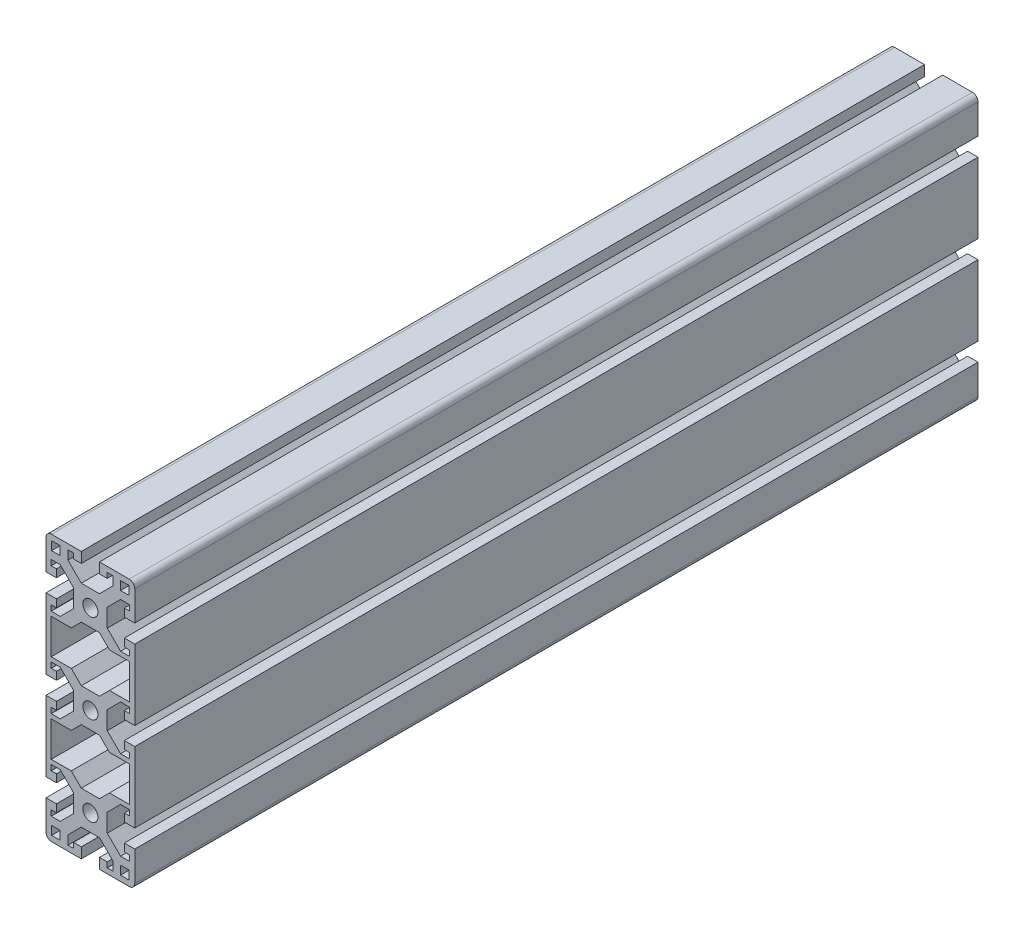
SolidWorks part; units mm, degrees
material "6063-T6"
ref_plane "Front Plane" through (0, 0, 0) normal (0, 0, 1) x (1, 0, 0)
ref_plane "Top Plane" through (0, 0, 0) normal (0, 1, 0) x (1, 0, 0)
ref_plane "Right Plane" through (0, 0, 0) normal (1, 0, 0) x (0, 0, -1)
sketch "Sketch1" plane through (0, 0, 0) normal (0, 1, 0) x (1, 0, 0)
  line L0 (0, 190) -> (0, -190)
  dimension "D1" = 380
other "40 series TS40-120LM(1)"
ref_plane "Plane1" through (0, 0, -190) normal (0, 0, 1) x (1, 0, 0)
sketch "Sketch2" plane through (0, 0, -190) normal (0, 0, 1) x (1, 0, 0)
  line L0 (15.3, -35.9) -> (20, -35.9)
  line L1 (3.35, 0) -> (7.6, 0) construction
  line L2 (7.6, 4.1) -> (7.6, -4.1)
  line L3 (7.6, -4.1) -> (13.6, -10.1)
  line L4 (13.6, -10.1) -> (17.65, -10.1)
  line L5 (17.65, -10.1) -> (17.65, -7.6)
  line L6 (17.65, -7.6) -> (15.3, -7.6)
  line L7 (15.3, -7.6) -> (15.3, -4.1)
  line L8 (15.3, -4.1) -> (20, -4.1)
  line L9 (20, -4.1) -> (20, -35.9)
  line L10 (0, -3.35) -> (0, -7.6) construction
  line L11 (-4.1, -7.6) -> (4.1, -7.6)
  line L12 (4.1, -7.6) -> (8.6, -12.1)
  line L13 (8.6, -12.1) -> (17.65, -12.1)
  line L14 (17.65, -12.1) -> (17.65, -27.9)
  line L15 (20, -20) -> (0, 0) construction
  line L16 (17.65, -20) -> (20, -20) construction
  line L17 (15.3, -32.4) -> (15.3, -35.9)
  line L18 (17.65, -32.4) -> (15.3, -32.4)
  line L19 (17.65, -29.9) -> (17.65, -32.4)
  line L20 (13.6, -29.9) -> (17.65, -29.9)
  line L21 (8.6, -27.9) -> (17.65, -27.9)
  line L22 (7.6, -35.9) -> (13.6, -29.9)
  line L23 (7.6, -44.1) -> (7.6, -35.9)
  line L24 (4.1, -32.4) -> (8.6, -27.9)
  line L25 (-4.1, -32.4) -> (4.1, -32.4)
  line L26 (3.35, -40) -> (7.6, -40) construction
  line L27 (15.3, -44.1) -> (20, -44.1)
  line L28 (15.3, -47.6) -> (15.3, -44.1)
  line L29 (17.65, -47.6) -> (15.3, -47.6)
  line L30 (17.65, -50.1) -> (17.65, -47.6)
  line L31 (13.6, -50.1) -> (17.65, -50.1)
  line L32 (7.6, -44.1) -> (13.6, -50.1)
  line L33 (0, -40) -> (19.2678, -59.2678) construction
  line L34 (20, -57.5) -> (20, -44.1)
  line L35 (17.5, -60) -> (4.1, -60)
  line L36 (4.1, -55.3) -> (4.1, -60)
  line L37 (7.6, -55.3) -> (4.1, -55.3)
  line L38 (7.6, -57.65) -> (7.6, -55.3)
  line L39 (10.1, -57.65) -> (7.6, -57.65)
  line L40 (10.1, -53.6) -> (10.1, -57.65)
  line L41 (4.1, -47.6) -> (10.1, -53.6)
  line L42 (4.1, -47.6) -> (-4.1, -47.6)
  line L43 (0, -40) -> (-19.2678, -59.2678) construction
  line L44 (-3.35, -40) -> (-7.6, -40) construction
  line L45 (-17.65, -20) -> (-20, -20) construction
  line L46 (-20, -20) -> (0, 0) construction
  line L47 (-3.35, 0) -> (-7.6, 0) construction
  line L48 (-4.1, -47.6) -> (-10.1, -53.6)
  line L49 (-10.1, -53.6) -> (-10.1, -57.65)
  line L50 (-10.1, -57.65) -> (-7.6, -57.65)
  line L51 (-7.6, -57.65) -> (-7.6, -55.3)
  line L52 (-7.6, -55.3) -> (-4.1, -55.3)
  line L53 (-4.1, -55.3) -> (-4.1, -60)
  line L54 (-17.5, -60) -> (-4.1, -60)
  line L55 (-20, -57.5) -> (-20, -44.1)
  line L56 (-7.6, -44.1) -> (-13.6, -50.1)
  line L57 (-13.6, -50.1) -> (-17.65, -50.1)
  line L58 (-17.65, -50.1) -> (-17.65, -47.6)
  line L59 (-17.65, -47.6) -> (-15.3, -47.6)
  line L60 (-15.3, -47.6) -> (-15.3, -44.1)
  line L61 (-15.3, -44.1) -> (-20, -44.1)
  line L62 (-4.1, -32.4) -> (-8.6, -27.9)
  line L63 (-7.6, -44.1) -> (-7.6, -35.9)
  line L64 (-7.6, -35.9) -> (-13.6, -29.9)
  line L65 (-8.6, -27.9) -> (-17.65, -27.9)
  line L66 (-13.6, -29.9) -> (-17.65, -29.9)
  line L67 (-17.65, -29.9) -> (-17.65, -32.4)
  line L68 (-17.65, -32.4) -> (-15.3, -32.4)
  line L69 (-15.3, -32.4) -> (-15.3, -35.9)
  line L70 (-17.65, -12.1) -> (-17.65, -27.9)
  line L71 (-8.6, -12.1) -> (-17.65, -12.1)
  line L72 (-4.1, -7.6) -> (-8.6, -12.1)
  line L73 (-20, -4.1) -> (-20, -35.9)
  line L74 (-15.3, -4.1) -> (-20, -4.1)
  line L75 (-15.3, -7.6) -> (-15.3, -4.1)
  line L76 (-17.65, -7.6) -> (-15.3, -7.6)
  line L77 (-17.65, -10.1) -> (-17.65, -7.6)
  line L78 (-13.6, -10.1) -> (-17.65, -10.1)
  line L79 (-7.6, -4.1) -> (-13.6, -10.1)
  line L80 (-7.6, 4.1) -> (-7.6, -4.1)
  line L81 (-15.3, -35.9) -> (-20, -35.9)
  line L82 (-20, 20) -> (0, 0) construction
  line L83 (-17.65, 20) -> (-20, 20) construction
  line L84 (-3.35, 40) -> (-7.6, 40) construction
  line L85 (0, 40) -> (-19.2678, 59.2678) construction
  line L86 (0, 40) -> (19.2678, 59.2678) construction
  line L87 (3.35, 40) -> (7.6, 40) construction
  line L88 (17.65, 20) -> (20, 20) construction
  line L89 (20, 20) -> (0, 0) construction
  line L90 (0, 3.35) -> (0, 7.6) construction
  line L91 (-15.3, 35.9) -> (-20, 35.9)
  line L92 (-7.6, 4.1) -> (-13.6, 10.1)
  line L93 (-13.6, 10.1) -> (-17.65, 10.1)
  line L94 (-17.65, 10.1) -> (-17.65, 7.6)
  line L95 (-17.65, 7.6) -> (-15.3, 7.6)
  line L96 (-15.3, 7.6) -> (-15.3, 4.1)
  line L97 (-15.3, 4.1) -> (-20, 4.1)
  line L98 (-20, 4.1) -> (-20, 35.9)
  line L99 (-4.1, 7.6) -> (-8.6, 12.1)
  line L100 (-8.6, 12.1) -> (-17.65, 12.1)
  line L101 (-17.65, 12.1) -> (-17.65, 27.9)
  line L102 (-15.3, 32.4) -> (-15.3, 35.9)
  line L103 (-17.65, 32.4) -> (-15.3, 32.4)
  line L104 (-17.65, 29.9) -> (-17.65, 32.4)
  line L105 (-13.6, 29.9) -> (-17.65, 29.9)
  line L106 (-8.6, 27.9) -> (-17.65, 27.9)
  line L107 (-7.6, 35.9) -> (-13.6, 29.9)
  line L108 (-7.6, 44.1) -> (-7.6, 35.9)
  line L109 (-4.1, 32.4) -> (-8.6, 27.9)
  line L110 (-15.3, 44.1) -> (-20, 44.1)
  line L111 (-15.3, 47.6) -> (-15.3, 44.1)
  line L112 (-17.65, 47.6) -> (-15.3, 47.6)
  line L113 (-17.65, 50.1) -> (-17.65, 47.6)
  line L114 (-13.6, 50.1) -> (-17.65, 50.1)
  line L115 (-7.6, 44.1) -> (-13.6, 50.1)
  line L116 (-20, 57.5) -> (-20, 44.1)
  line L117 (-17.5, 60) -> (-4.1, 60)
  line L118 (-4.1, 55.3) -> (-4.1, 60)
  line L119 (-7.6, 55.3) -> (-4.1, 55.3)
  line L120 (-7.6, 57.65) -> (-7.6, 55.3)
  line L121 (-10.1, 57.65) -> (-7.6, 57.65)
  line L122 (-10.1, 53.6) -> (-10.1, 57.65)
  line L123 (-4.1, 47.6) -> (-10.1, 53.6)
  line L124 (4.1, 47.6) -> (-4.1, 47.6)
  line L125 (4.1, 47.6) -> (10.1, 53.6)
  line L126 (10.1, 53.6) -> (10.1, 57.65)
  line L127 (10.1, 57.65) -> (7.6, 57.65)
  line L128 (7.6, 57.65) -> (7.6, 55.3)
  line L129 (7.6, 55.3) -> (4.1, 55.3)
  line L130 (4.1, 55.3) -> (4.1, 60)
  line L131 (17.5, 60) -> (4.1, 60)
  line L132 (20, 57.5) -> (20, 44.1)
  line L133 (7.6, 44.1) -> (13.6, 50.1)
  line L134 (13.6, 50.1) -> (17.65, 50.1)
  line L135 (17.65, 50.1) -> (17.65, 47.6)
  line L136 (17.65, 47.6) -> (15.3, 47.6)
  line L137 (15.3, 47.6) -> (15.3, 44.1)
  line L138 (15.3, 44.1) -> (20, 44.1)
  line L139 (-4.1, 32.4) -> (4.1, 32.4)
  line L140 (4.1, 32.4) -> (8.6, 27.9)
  line L141 (7.6, 44.1) -> (7.6, 35.9)
  line L142 (7.6, 35.9) -> (13.6, 29.9)
  line L143 (8.6, 27.9) -> (17.65, 27.9)
  line L144 (13.6, 29.9) -> (17.65, 29.9)
  line L145 (17.65, 29.9) -> (17.65, 32.4)
  line L146 (17.65, 32.4) -> (15.3, 32.4)
  line L147 (15.3, 32.4) -> (15.3, 35.9)
  line L148 (17.65, 12.1) -> (17.65, 27.9)
  line L149 (8.6, 12.1) -> (17.65, 12.1)
  line L150 (4.1, 7.6) -> (8.6, 12.1)
  line L151 (-4.1, 7.6) -> (4.1, 7.6)
  line L152 (20, 4.1) -> (20, 35.9)
  line L153 (15.3, 4.1) -> (20, 4.1)
  line L154 (15.3, 7.6) -> (15.3, 4.1)
  line L155 (17.65, 7.6) -> (15.3, 7.6)
  line L156 (17.65, 10.1) -> (17.65, 7.6)
  line L157 (13.6, 10.1) -> (17.65, 10.1)
  line L158 (7.6, 4.1) -> (13.6, 10.1)
  line L159 (15.3, 35.9) -> (20, 35.9)
  line L161 (13.6, -53.6) -> (17.5, -53.6)
  line L162 (13.6, -53.6) -> (13.6, -57.5)
  line L163 (13.6, -57.5) -> (17.5, -57.5)
  line L164 (17.5, -53.6) -> (17.5, -57.5)
  line L165 (-17.5, -57.5) -> (-13.6, -57.5)
  line L166 (-17.5, -57.5) -> (-17.5, -53.6)
  line L167 (-17.5, -53.6) -> (-13.6, -53.6)
  line L168 (-13.6, -57.5) -> (-13.6, -53.6)
  line L169 (-17.5, 57.5) -> (-13.6, 57.5)
  line L170 (-17.5, 57.5) -> (-17.5, 53.6)
  line L171 (-17.5, 53.6) -> (-13.6, 53.6)
  line L172 (-13.6, 57.5) -> (-13.6, 53.6)
  line L173 (17.5, 57.5) -> (13.6, 57.5)
  line L174 (17.5, 57.5) -> (17.5, 53.6)
  line L175 (17.5, 53.6) -> (13.6, 53.6)
  line L176 (13.6, 57.5) -> (13.6, 53.6)
  arc A0 (0, -43.35) -> (0, -36.65) centre (0, -40) ccw
  arc A1 (3.35, 0) -> (-3.35, 0) centre (0, 0) cw
  arc A2 (17.5, -60) -> (20, -57.5) centre (17.5, -57.5) ccw
  arc A3 (-17.5, -60) -> (-20, -57.5) centre (-17.5, -57.5) cw
  arc A4 (0, -43.35) -> (0, -36.65) centre (0, -40) cw
  arc A5 (0, 43.35) -> (0, 36.65) centre (0, 40) ccw
  arc A6 (-17.5, 60) -> (-20, 57.5) centre (-17.5, 57.5) ccw
  arc A7 (17.5, 60) -> (20, 57.5) centre (17.5, 57.5) cw
  arc A8 (3.35, 0) -> (-3.35, 0) centre (0, 0) ccw
  arc A9 (0, 43.35) -> (0, 36.65) centre (0, 40) cw
  point P19 (17.65, -4.1)
  point P65 (0, -47.6)
  point P79 (0, -32.4)
  point P196 (0, 32.4)
  point P197 (0, 47.6)
  point P201 (20, -60)
  point P202 (-20, -60)
  point P203 (20, -40)
  point P204 (-20, -40)
  point P205 (20, -20)
  point P206 (0, -60)
  point P207 (0, -40)
  point P208 (-20, -20)
  point P209 (-20, 0)
  point P210 (20, 0)
  point P211 (20, 40)
  point P212 (0, 0)
  point P213 (-20, 20)
  point P214 (20, 20)
  point P215 (-20, 40)
  point P216 (0, 40)
  point P217 (20, 60)
  point P218 (0, 60)
  point P219 (-20, 60)
  point P220 (0, 20)
  point P221 (0, -20)
  point P222 (0, 0)
  dimension "D2" = 4.1
  dimension "D4" = 12.4
  dimension "D9" = 2.5
  dimension "D3" = 3.35
  dimension "D5" = 20
  dimension "D10" = 20
  dimension "D6" = 10.1
  dimension "D8" = 2
  dimension "D11" = 2.5
  dimension "D7" = 4.7
hole_wizard "M8x1.25 Tapped Hole1" positions "Sketch3" profile "Sketch4" tap size "M8x1.25" standard "ANSI Metric"
sketch "Sketch3" plane through (0, 0, 190) normal (0, 0, 1) x (1, 0, 0)
  point P0 (0, 40)
  point P3 (0, 0)
  point P6 (0, -40)
sketch "Sketch4" plane through (0, 40, 190) normal (1, 0, 0) x (0, -1, 0)
  line L0 (0, 0) -> (0, 27.0429)
  line L1 (0, 27.0429) -> (3.4, 25)
  line L2 (3.4, 25) -> (3.4, 0)
  line L5 (3.4, 0) -> (0, 0)
  line L10 (0, 27.0429) -> (-3.4, 25) construction
  line L11 (0, -6.35) -> (0, 107.95) construction
  dimension "Tap Drill Dia." = 6.8
  dimension "Tap Drill Depth" = 25
  dimension "Drill Angle" = 118
cosmetic thread "Hole Thread1" parameters "D1"=20, "D2"=8
cosmetic thread "Hole Thread2" parameters "D1"=20, "D2"=8
cosmetic thread "Hole Thread3" parameters "D1"=20, "D2"=8
mirror "Mirror1" about plane through (0, 0, 0) normal (0, 0, 1) of "M8x1.25 Tapped Hole1"
cosmetic thread "Hole Thread4" parameters "D1"=20, "D2"=8
cosmetic thread "Hole Thread5" parameters "D1"=20, "D2"=8
cosmetic thread "Hole Thread6" parameters "D1"=20, "D2"=8
